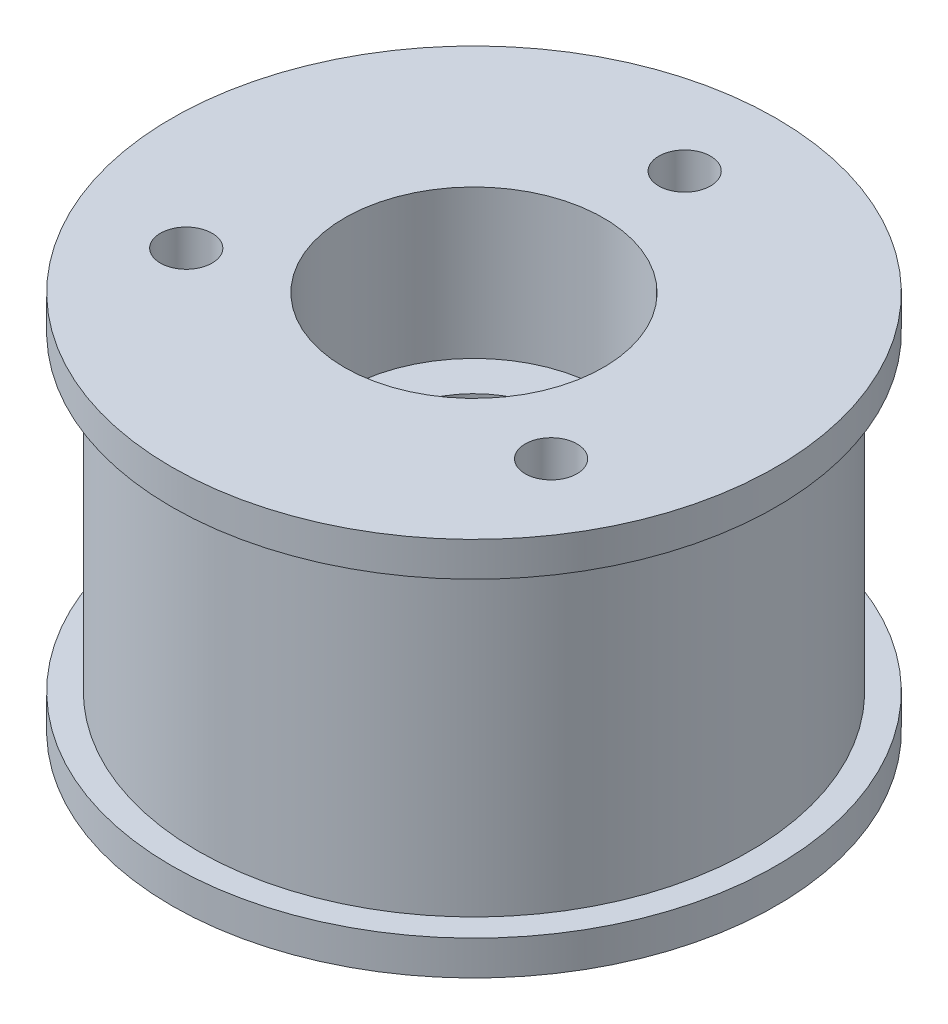
SolidWorks part; units mm, degrees
material "PA Type 6"
ref_plane "Front Plane" through (0, 0, 0) normal (0, 0, 1) x (1, 0, 0)
ref_plane "Top Plane" through (0, 0, 0) normal (0, 1, 0) x (1, 0, 0)
ref_plane "Right Plane" through (0, 0, 0) normal (1, 0, 0) x (0, 0, -1)
sketch "Sketch1" plane through (0, 0, 0) normal (0, 1, 0) x (1, 0, 0)
  circle A0 centre (0, 0) radius 17.5
  dimension "D1" = 35
extrude "Boss-Extrude1" add sketch "Sketch1" along normal blind 22
sketch "Sketch2" plane through (0, 22, 0) normal (0, 1, 0) x (1, 0, 0)
  point P0 (0, 0)
hole_wizard "CBORE for M8 Hex Socket Head Cap Screw1" positions "Sketch2" profile "Sketch3" counterbore size "M8" standard "DIN" end condition through all
sketch "Sketch3" plane through (0, 22, 0) normal (1, 0, 0) x (0, 0, 1)
  line L0 (0, 0) -> (0, 22)
  line L1 (0, 22) -> (5, 22)
  line L3 (5, 22) -> (5, 8.6)
  line L4 (5, 8.6) -> (7.5, 8.6)
  line L5 (7.5, 8.6) -> (7.5, 0)
  line L7 (7.5, 0) -> (0, 0)
  line L11 (0, -6.35) -> (0, 107.95) construction
  dimension "Thru Hole Dia." = 10
  dimension "Thru Hole Depth" = 22
  dimension "C'Bore Dia." = 15
  dimension "C'Bore Depth" = 8.6
sketch "Sketch4" plane through (0, 22, 0) normal (0, 1, 0) x (1, 0, 0)
  circle A0 centre (0, 0) radius 12.2
  point P4 (0, 12.2)
  point P9 (10.5655, -6.1)
  point P10 (-10.5655, -6.1)
  dimension "D1" = 24.4
  dimension "D2" = 3
hole_wizard "Ø3.0mm Dowel Hole1" positions "Sketch4" profile "Sketch5" hole size "Ø3.0" standard "DIN" end condition through all
sketch "Sketch5" plane through (-10.5655, 22, 6.1) normal (1, 0, 0) x (0, 0, 1)
  line L0 (0, 0) -> (0, 22)
  line L1 (0, 22) -> (1.5, 22)
  line L2 (1.5, 22) -> (1.5, 0)
  line L5 (1.5, 0) -> (0, 0)
  line L11 (0, -6.35) -> (0, 107.95) construction
  dimension "Thru Hole Dia." = 3
  dimension "Thru Hole Depth" = 22
sketch "Sketch6" plane through (0, 0, 0) normal (0, -1, 0) x (1, 0, 0)
  circle A0 centre (0, 0) radius 8.5
  dimension "D1" = 17
extrude "Cut-Extrude1" cut sketch "Sketch6" against normal blind 3.5
sketch "Sketch7" plane through (0, 0, 0) normal (0, -1, 0) x (1, 0, 0)
  circle A0 centre (0, 0) radius 16
  circle A1 centre (0, 0) radius 17.5 construction
  circle A2 centre (0, 0) radius 17.5
  dimension "D1" = 32
extrude "Cut-Extrude2" cut sketch "Sketch7" against normal blind 18 from offset 2
